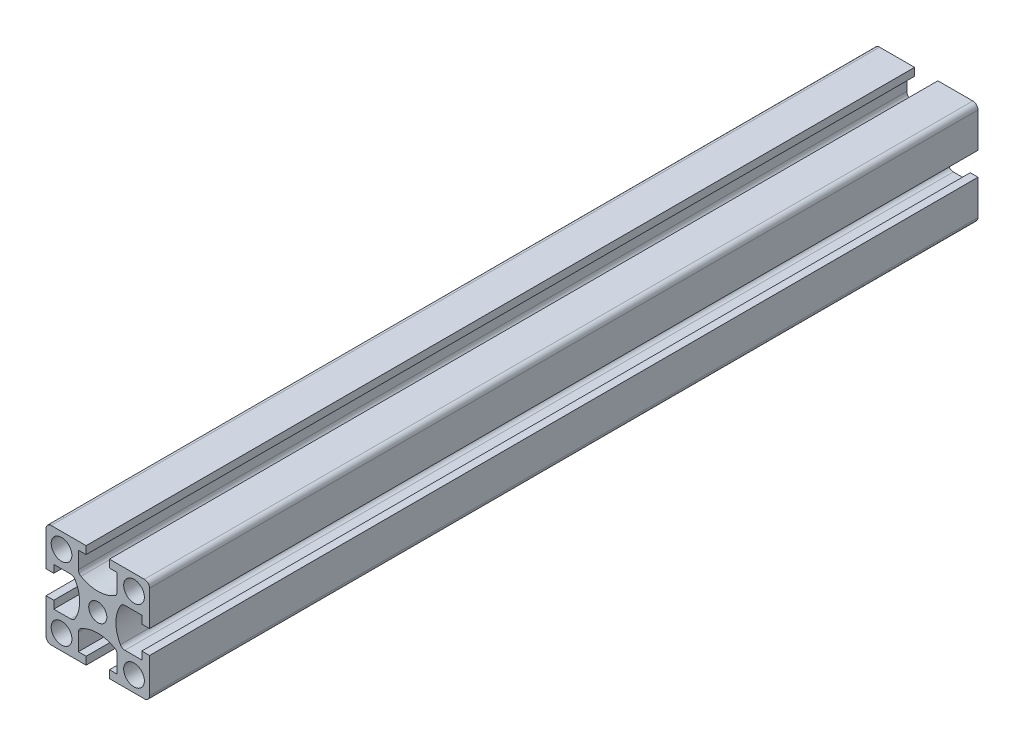
SolidWorks part; units mm, degrees
ref_plane "Front Plane" through (0, 0, 0) normal (0, 0, 1) x (1, 0, 0)
ref_plane "Top Plane" through (0, 0, 0) normal (0, 1, 0) x (1, 0, 0)
ref_plane "Right Plane" through (0, 0, 0) normal (1, 0, 0) x (0, 0, -1)
sketch "Sketch1" plane through (0, 0, 0) normal (0, 0, 1) x (1, 0, 0)
  line L64 (-25, 22.5) -> (-25, 5.625)
  line L65 (-25, 5.625) -> (-21.25, 5.625)
  line L66 (-21.25, 5.625) -> (-21.25, 9.375)
  line L67 (-21.25, 9.375) -> (-13.0922, 9.375)
  line L68 (-13.0922, -9.375) -> (-21.25, -9.375)
  line L69 (-21.25, -9.375) -> (-21.25, -5.625)
  line L70 (-21.25, -5.625) -> (-25, -5.625)
  line L71 (-25, -5.625) -> (-25, -22.5)
  line L72 (-22.5, -25) -> (-5.625, -25)
  line L73 (-5.625, -25) -> (-5.625, -21.25)
  line L74 (-5.625, -21.25) -> (-9.375, -21.25)
  line L75 (-9.375, -21.25) -> (-9.375, -13.0922)
  line L76 (9.375, -13.0922) -> (9.375, -21.25)
  line L77 (9.375, -21.25) -> (5.625, -21.25)
  line L78 (5.625, -21.25) -> (5.625, -25)
  line L79 (5.625, -25) -> (22.5, -25)
  line L80 (25, -22.5) -> (25, -5.625)
  line L81 (25, -5.625) -> (21.25, -5.625)
  line L82 (21.25, -5.625) -> (21.25, -9.375)
  line L83 (21.25, -9.375) -> (13.0922, -9.375)
  line L84 (13.0922, 9.375) -> (21.25, 9.375)
  line L85 (21.25, 9.375) -> (21.25, 5.625)
  line L86 (21.25, 5.625) -> (25, 5.625)
  line L87 (25, 5.625) -> (25, 22.5)
  line L88 (22.5, 25) -> (5.625, 25)
  line L89 (5.625, 25) -> (5.625, 21.25)
  line L90 (5.625, 21.25) -> (9.375, 21.25)
  line L91 (9.375, 21.25) -> (9.375, 13.0922)
  line L92 (-9.375, 13.0922) -> (-9.375, 21.25)
  line L93 (-9.375, 21.25) -> (-5.625, 21.25)
  line L94 (-5.625, 21.25) -> (-5.625, 25)
  line L95 (-5.625, 25) -> (-22.5, 25)
  circle A5 centre (-17.5, -17.5) radius 5
  circle A6 centre (17.5, -17.5) radius 5
  circle A7 centre (17.5, 17.5) radius 5
  circle A8 centre (0, 0) radius 4.375
  circle A9 centre (-17.5, 17.5) radius 5
  arc A32 (-22.5, 25) -> (-25, 22.5) centre (-22.5, 22.5) ccw
  arc A33 (-10.9271, 8.125) -> (-13.0922, 9.375) centre (-13.0922, 6.875) ccw
  arc A34 (-10.9271, -8.125) -> (-10.9271, 8.125) centre (-25, 0) ccw
  arc A35 (-13.0922, -9.375) -> (-10.9271, -8.125) centre (-13.0922, -6.875) ccw
  arc A36 (-25, -22.5) -> (-22.5, -25) centre (-22.5, -22.5) ccw
  arc A37 (-8.125, -10.9271) -> (-9.375, -13.0922) centre (-6.875, -13.0922) ccw
  arc A38 (8.125, -10.9271) -> (-8.125, -10.9271) centre (0, -25) ccw
  arc A39 (9.375, -13.0922) -> (8.125, -10.9271) centre (6.875, -13.0922) ccw
  arc A40 (22.5, -25) -> (25, -22.5) centre (22.5, -22.5) ccw
  arc A41 (10.9271, -8.125) -> (13.0922, -9.375) centre (13.0922, -6.875) ccw
  arc A42 (10.9271, 8.125) -> (10.9271, -8.125) centre (25, 0) ccw
  arc A43 (13.0922, 9.375) -> (10.9271, 8.125) centre (13.0922, 6.875) ccw
  arc A44 (25, 22.5) -> (22.5, 25) centre (22.5, 22.5) ccw
  arc A45 (8.125, 10.9271) -> (9.375, 13.0922) centre (6.875, 13.0922) ccw
  arc A46 (-8.125, 10.9271) -> (8.125, 10.9271) centre (0, 25) ccw
  arc A47 (-9.375, 13.0922) -> (-8.125, 10.9271) centre (-6.875, 13.0922) ccw
  dimension "D3" = 10
  dimension "D4" = 8.75
  dimension "D8" = 16.25
  dimension "D9" = 2.5
  dimension "D15" = 16.25
  dimension "D1" = 50
  dimension "D2" = 50
  dimension "D5" = 19.375
  dimension "D6" = 19.375
  dimension "D7" = 3.75
  dimension "D10" = 8.1578
  dimension "D11" = 3.75
  dimension "D12" = 8.1578
  dimension "D13" = 3.75
  dimension "D14" = 3.75
extrude "Boss-Extrude1" add sketch "Sketch1" along normal blind 400
